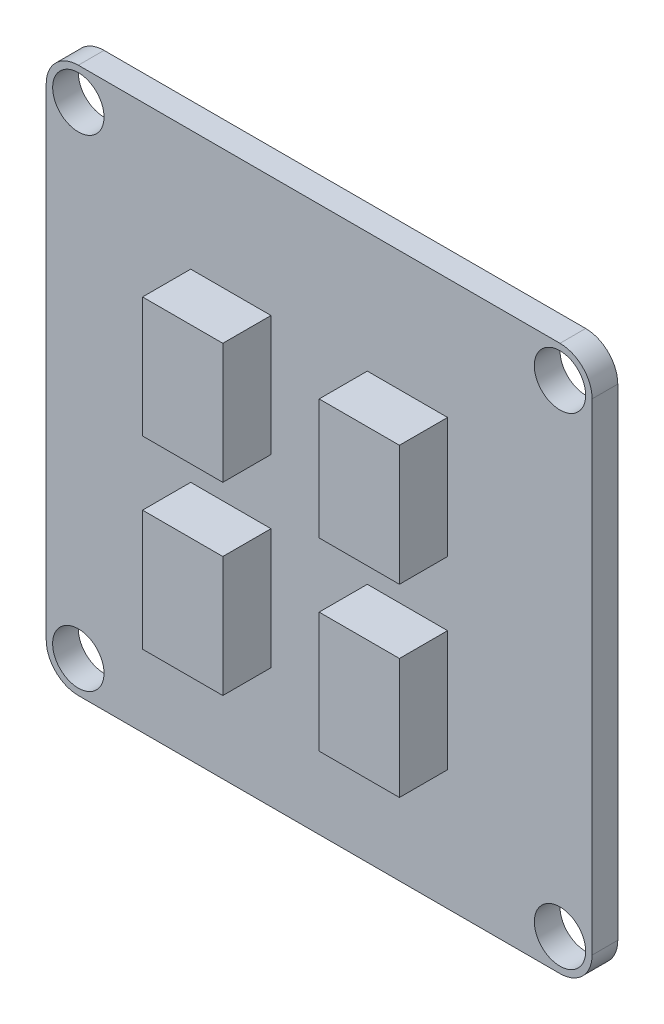
SolidWorks part; units mm, degrees
ref_plane "Front Plane" through (0, 0, 0) normal (0, 0, 1) x (1, 0, 0)
ref_plane "Top Plane" through (0, 0, 0) normal (0, 1, 0) x (1, 0, 0)
ref_plane "Right Plane" through (0, 0, 0) normal (1, 0, 0) x (0, 0, -1)
sketch "Sketch1" plane through (0, 0, 0) normal (0, 0, 1) x (1, 0, 0)
  line L0 (1.7643, 13.6116) -> (1.7643, -20.3884) construction
  line L1 (-13.2357, 13.6116) -> (16.7643, 13.6116)
  line L2 (-15.2357, 11.6116) -> (-15.2357, -18.3884)
  line L3 (-13.2357, -20.3884) -> (16.7643, -20.3884)
  line L4 (18.7643, 11.6116) -> (18.7643, -18.3884)
  line L5 (-15.2357, -3.3884) -> (18.7643, -3.3884) construction
  circle A0 centre (16.7643, 11.6116) radius 1.6
  arc A1 (-13.2357, 13.6116) -> (-15.2357, 11.6116) centre (-13.2357, 11.6116) ccw
  arc A2 (-15.2357, -18.3884) -> (-13.2357, -20.3884) centre (-13.2357, -18.3884) ccw
  arc A3 (16.7643, -20.3884) -> (18.7643, -18.3884) centre (16.7643, -18.3884) ccw
  arc A4 (16.7643, 13.6116) -> (18.7643, 11.6116) centre (16.7643, 11.6116) cw
  circle A5 centre (16.7643, -18.3884) radius 1.6
  circle A6 centre (-13.2357, 11.6116) radius 1.6
  circle A7 centre (-13.2357, -18.3884) radius 1.6
  point P12 (-15.2357, 13.6116)
  point P17 (18.7643, -20.3884)
  point P20 (18.7643, 13.6116)
  dimension "D3" = 2
extrude "Boss-Extrude1" add sketch "Sketch1" along normal blind 1.6
sketch "Sketch2" plane through (0, 0, 1.6) normal (0, 0, 1) x (1, 0, 0)
  line L0 (1.7643, 13.6116) -> (1.7643, -20.5513) construction
  line L1 (9.7643, 6.1116) -> (4.7643, 6.1116)
  line L2 (9.7643, 6.1116) -> (9.7643, -1.3884)
  line L3 (9.7643, -1.3884) -> (4.7643, -1.3884)
  line L4 (4.7643, 6.1116) -> (4.7643, -1.3884)
  line L5 (9.7643, -5.3884) -> (4.7643, -5.3884)
  line L6 (9.7643, -5.3884) -> (9.7643, -12.8884)
  line L7 (9.7643, -12.8884) -> (4.7643, -12.8884)
  line L8 (4.7643, -5.3884) -> (4.7643, -12.8884)
  line L9 (16.7643, 13.6116) -> (-13.2357, 13.6116) construction
  line L10 (1.7643, -3.3884) -> (18.7643, -3.3884) construction
  line L11 (18.7643, -18.3884) -> (18.7643, 11.6116) construction
  line L12 (-1.2357, -5.3884) -> (-1.2357, -12.8884)
  line L13 (-6.2357, -12.8884) -> (-1.2357, -12.8884)
  line L14 (-6.2357, -5.3884) -> (-6.2357, -12.8884)
  line L15 (-6.2357, -5.3884) -> (-1.2357, -5.3884)
  line L16 (-1.2357, 6.1116) -> (-1.2357, -1.3884)
  line L17 (-6.2357, -1.3884) -> (-1.2357, -1.3884)
  line L18 (-6.2357, 6.1116) -> (-6.2357, -1.3884)
  line L19 (-6.2357, 6.1116) -> (-1.2357, 6.1116)
extrude "Boss-Extrude2" add sketch "Sketch2" along normal blind 3
